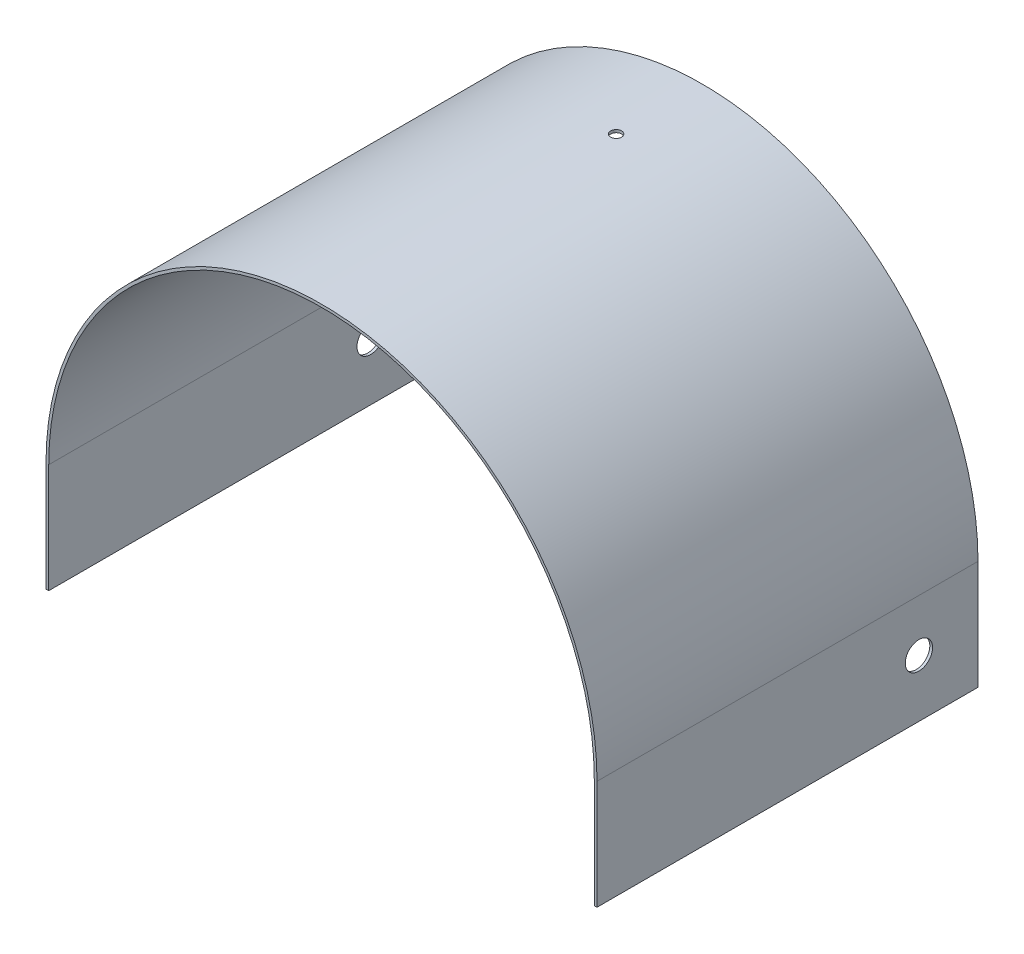
SolidWorks part; units mm, degrees
ref_plane "前视基准面" through (0, 0, 0) normal (0, 0, 1) x (1, 0, 0)
ref_plane "上视基准面" through (0, 0, 0) normal (0, 1, 0) x (1, 0, 0)
ref_plane "右视基准面" through (0, 0, 0) normal (1, 0, 0) x (0, 0, -1)
sketch "草图1" plane through (0, 0, 0) normal (0, 0, 1) x (1, 0, 0)
  line L6 (-300, 0) -> (-300, -120)
  line L10 (300, -120) -> (300, 0)
  line L11 (-303, 0) -> (-303, -120)
  line L13 (303, -120) -> (303, 0)
  line L14 (-300, -120) -> (-303, -120)
  line L15 (300, -120) -> (303, -120)
  line L16 (303, -123) -> (303, 0) construction
  line L17 (-303, -123) -> (303, -123) construction
  line L18 (-303, 0) -> (-303, -123) construction
  line L19 (-300, -120) -> (300, -120) construction
  arc A2 (300, 0) -> (-300, 0) centre (0, 0) ccw
  arc A3 (303, 0) -> (-303, 0) centre (0, 0) ccw
  dimension "D1" = 600
  dimension "D2" = 120
  dimension "D3" = 3
extrude "凸台-拉伸2" add sketch "草图1" along normal blind 419
sketch "草图2" plane through (0, 0, 0) normal (0, 1, 0) x (1, 0, 0)
  circle A0 centre (0, -95) radius 6
  dimension "D2" = 12
  dimension "D1" = 95
extrude "切除-拉伸1" cut sketch "草图2" along normal blind 490
sketch "草图3" plane through (0, 0, 0) normal (1, 0, 0) x (0, 0, -1)
  line L0 (-419, -120) -> (0, -120) construction
  line L1 (0, -120) -> (0, 0) construction
  circle A0 centre (-65, -57.08) radius 15
  dimension "D2" = 30
  dimension "D1" = 62.92
  dimension "D3" = 65
extrude "切除-拉伸2" cut sketch "草图3" against normal mid plane 1000
